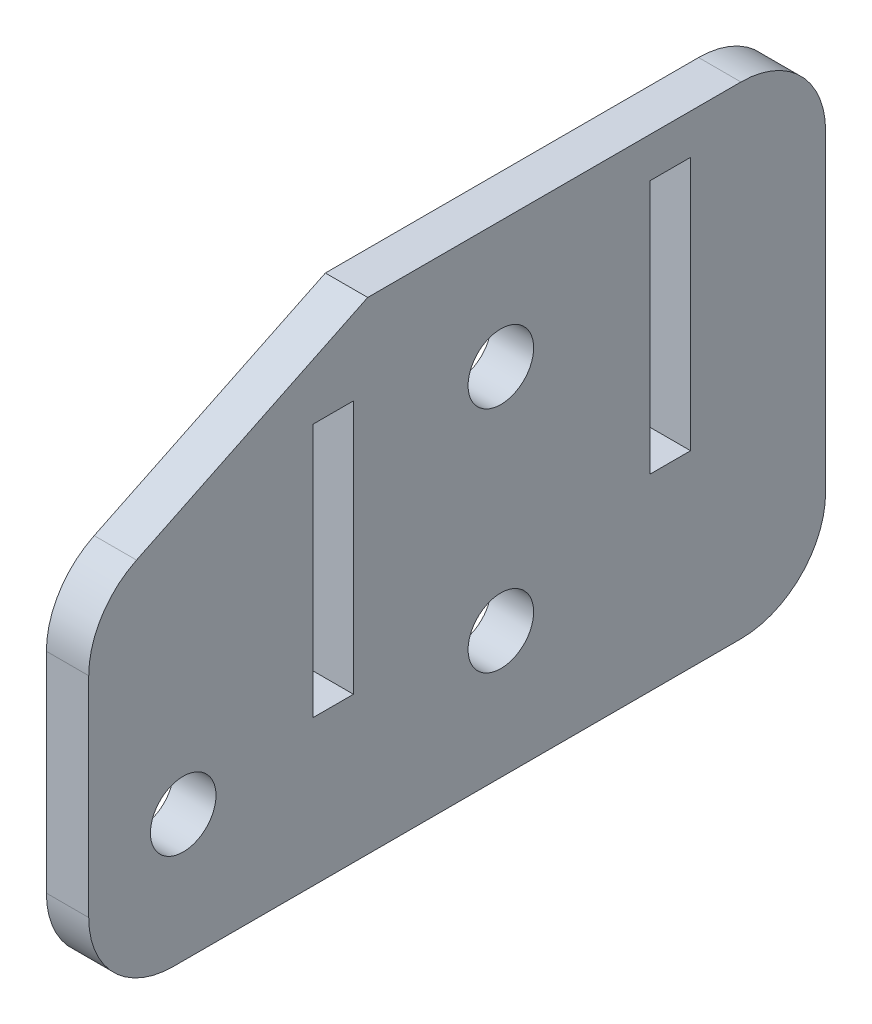
SolidWorks part; units mm, degrees
material "AISI 4340 Steel, annealed"
ref_plane "X-Y Datum" through (0, 0, 0) normal (0, 0, 1) x (1, 0, 0)
ref_plane "X-Z Datum" through (0, 0, 0) normal (0, 1, 0) x (1, 0, 0)
ref_plane "Y-Z Datum" through (0, 0, 0) normal (1, 0, 0) x (0, 0, -1)
sketch "Sketch1" plane through (0, 0, 0) normal (1, 0, 0) x (0, 0, -1)
  line L13 (55.245, 0) -> (55.245, 36.1544)
  line L14 (55.245, 36.1544) -> (20.9147, 36.1544)
  line L15 (20.9147, 36.1544) -> (0, 26.034)
  line L16 (0, 26.034) -> (0, 0)
  line L17 (0, 0) -> (55.245, 0)
  point P4 (0, 0)
  point P6 (0, 13.017)
  point P7 (0, 0)
  dimension "D1" = 55.245
  dimension "D2" = 36.1544
  dimension "D3" = 20.9147
  dimension "D4" = 26.034
extrude "Boss-Extrude1" add sketch "Sketch1" along normal blind 3.175
sketch "Sketch7" plane through (0, 0, 0) normal (-1, 0, 0) x (0, 0, 1)
  line L8 (-55.245, 0) -> (-55.245, 36.1544) construction
  line L9 (-45.1202, 14.1002) -> (-42.0722, 14.1002)
  line L10 (-45.1202, 14.1002) -> (-45.1202, 33.1502)
  line L11 (-45.1202, 33.1502) -> (-42.0722, 33.1502)
  line L20 (-42.0722, 14.1002) -> (-42.0722, 33.1502)
  line L21 (-19.8472, 10.9252) -> (-16.7992, 10.9252)
  line L22 (-19.8472, 10.9252) -> (-19.8472, 29.9752)
  line L23 (-19.8472, 29.9752) -> (-16.7992, 29.9752)
  line L24 (-16.7992, 10.9252) -> (-16.7992, 29.9752)
  line L25 (-55.245, 36.1544) -> (-20.9147, 36.1544) construction
  point P10 (-43.5962, 33.1502)
  dimension "D1" = 19.05
  dimension "D2" = 3.048
  dimension "D3" = 10.1248
  dimension "D4" = 3.175
  dimension "D5" = 22.225
  dimension "D6" = 3.0042
extrude "Cut-Extrude1" cut sketch "Sketch7" against normal blind 3.175
sketch "Sketch8" plane through (0, 0, 0) normal (-1, 0, 0) x (0, 0, 1)
  line L0 (0, 0) -> (-55.245, 0) construction
  line L1 (-42.0722, 14.1002) -> (-42.0722, 33.1502) construction
  point P0 (-30.8962, 9.525)
  point P1 (-30.8962, 26.67)
  point P2 (-7.0837, 9.525)
  dimension "D1" = 17.145
  dimension "D2" = 9.525
  dimension "D3" = 23.8125
  dimension "D4" = 11.176
fillet "Fillet1" radius 6.35 4 edges at (1.5875, 26.034, 0) (1.5875, 0, 0) (1.5875, 36.1544, -55.245) (1.5875, 0, -55.245)
hole_wizard "#10 (0.1935) Diameter Hole2" positions "Sketch9" profile "Sketch10" hole size "#10" standard "ANSI Inch"
sketch "Sketch9" plane through (0, 0, 0) normal (-1, 0, 0) x (0, 0, 1)
  point P0 (-30.8962, 9.525)
  point P3 (-30.8962, 26.67)
  point P6 (-7.0837, 9.525)
sketch "Sketch10" plane through (0, 9.525, -30.8962) normal (0, 1, 0) x (0, 0, 1)
  line L0 (0, 0) -> (0, 11.176)
  line L1 (0, 11.176) -> (2.4574, 9.6994)
  line L2 (2.4574, 9.6994) -> (2.4574, 0)
  line L5 (2.4574, 0) -> (0, 0)
  line L10 (0, 11.176) -> (-2.4575, 9.6994) construction
  line L11 (0, -6.35) -> (0, 107.95) construction
  dimension "Hole Dia." = 4.9149
  dimension "Hole Depth" = 11.176
  dimension "Drill Angle" = 118
